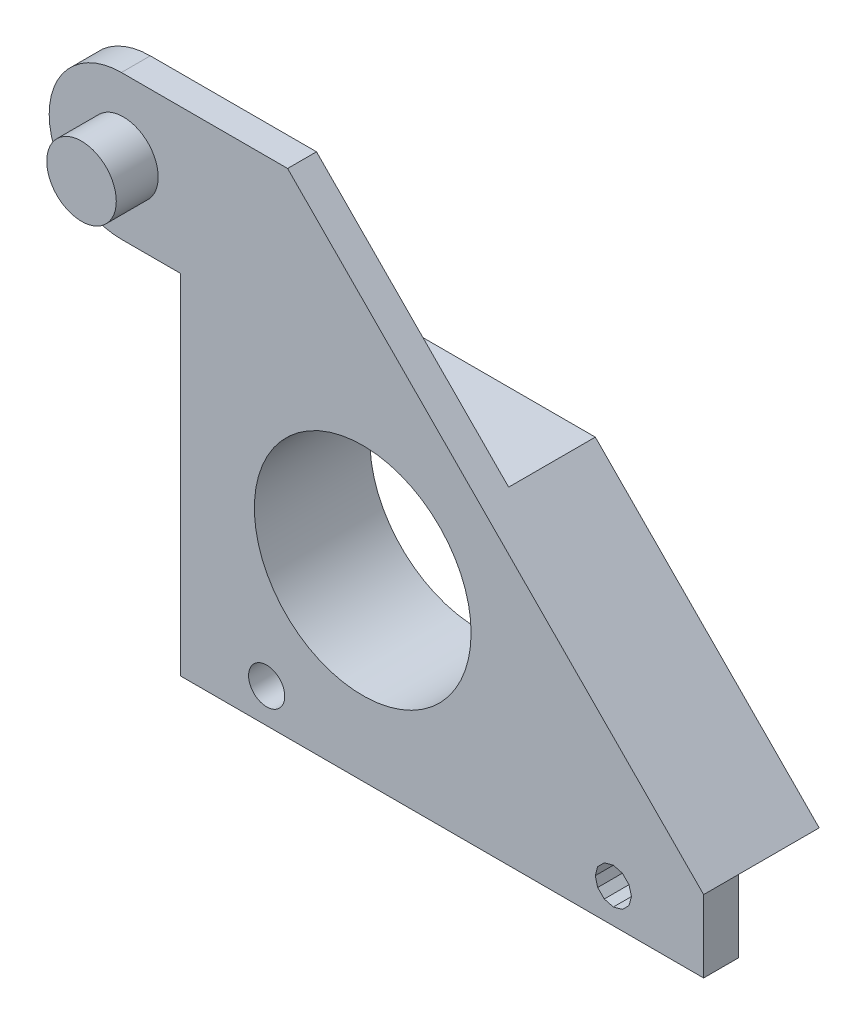
SolidWorks part; units mm, degrees
material "ABS"
ref_plane "Plan de face" through (0, 0, 0) normal (0, 0, 1) x (1, 0, 0)
ref_plane "Plan de dessus" through (0, 0, 0) normal (0, 1, 0) x (1, 0, 0)
ref_plane "Plan de droite" through (0, 0, 0) normal (1, 0, 0) x (0, 0, -1)
ref_plane "Plan1" through (0, 0, 2.4) normal (0, 0, 1) x (1, 0, 0)
sketch "Esquisse4" plane through (0, 0, 2.4) normal (0, 0, 1) x (1, 0, 0)
  line L0 (-20.1, -24.6348) -> (-48.9004, 4.5)
  line L1 (-48.9004, 4.5) -> (-60.4056, 4.5)
  line L2 (-60.4056, 4.5) -> (-61.692, 4.331) construction
  line L3 (-61.692, 4.331) -> (-62.899, 3.831) construction
  line L4 (-62.899, 3.831) -> (-63.935, 3.037) construction
  line L5 (-63.935, 3.037) -> (-64.73, 2.001) construction
  line L6 (-64.73, 2.001) -> (-65.3, 0.625) construction
  line L7 (-65.3, 0.625) -> (-65.3, -1.625) construction
  line L8 (-65.3, -1.625) -> (-64.73, -3.001) construction
  line L9 (-64.73, -3.001) -> (-63.935, -4.037) construction
  line L10 (-63.935, -4.037) -> (-62.899, -4.831) construction
  line L11 (-62.899, -4.831) -> (-61.692, -5.331) construction
  line L12 (-61.692, -5.331) -> (-60.4056, -5.5) construction
  line L13 (-60.4056, -5.5) -> (-56.3, -5.5)
  line L14 (-56.3, -5.5) -> (-56.3, -24.6348)
  line L15 (-56.3, -24.6348) -> (-20.1, -24.6348)
  arc A0 (-60.4056, 4.5) -> (-60.4056, -5.5) centre (-60.2989, -0.5) ccw
extrude "Boss.-Extru.1" add sketch "Esquisse4" against normal blind 2.4
ref_plane "Plan2" through (0, -24.6348, 0) normal (0, -1, 0) x (-1, 0, 0)
sketch "Esquisse9" plane through (0, -24.6348, 0) normal (0, -1, 0) x (-1, 0, 0)
  line L0 (56.3, -2.4) -> (20.1, -2.4)
  line L1 (20.1, -2.4) -> (20.1, 0)
  line L2 (20.1, 0) -> (56.3, 0)
  line L3 (56.3, 0) -> (56.3, -2.4)
extrude "Boss.-Extru.2" add sketch "Esquisse9" along normal blind 5
sketch "Esquisse14" plane through (0, 0, 2.4) normal (0, 0, 1) x (1, 0, 0)
  line L0 (-38.395, -22.305) -> (-37.462, -21.168) construction
  line L1 (-37.462, -21.168) -> (-36.769, -19.871) construction
  line L2 (-36.769, -19.871) -> (-36.342, -18.464) construction
  line L3 (-36.342, -18.464) -> (-36.198, -17) construction
  line L4 (-36.198, -17) -> (-36.7804, -14.9449) construction
  line L5 (-36.7804, -14.9449) -> (-37.2074, -13.5379) construction
  line L6 (-37.2074, -13.5379) -> (-37.9004, -12.2409) construction
  line L7 (-37.9004, -12.2409) -> (-38.3671, -11.6721) construction
  line L8 (-38.3671, -11.6721) -> (-39.532, -10.762) construction
  line L9 (-39.532, -10.762) -> (-40.829, -10.069) construction
  line L10 (-40.829, -10.069) -> (-42.236, -9.642) construction
  line L11 (-42.236, -9.642) -> (-43.7, -9.498) construction
  line L12 (-43.7, -9.498) -> (-45.164, -9.642) construction
  line L13 (-45.164, -9.642) -> (-46.571, -10.069) construction
  line L14 (-46.571, -10.069) -> (-47.868, -10.762) construction
  line L15 (-47.868, -10.762) -> (-49.005, -11.695) construction
  line L16 (-49.005, -11.695) -> (-49.938, -12.832) construction
  line L17 (-49.938, -12.832) -> (-50.631, -14.129) construction
  line L18 (-50.631, -14.129) -> (-51.058, -15.536) construction
  line L19 (-51.058, -15.536) -> (-51.203, -17) construction
  line L20 (-51.203, -17) -> (-51.058, -18.464) construction
  line L21 (-51.058, -18.464) -> (-50.631, -19.871) construction
  line L22 (-50.631, -19.871) -> (-49.938, -21.168) construction
  line L23 (-49.938, -21.168) -> (-49.005, -22.305) construction
  line L24 (-49.005, -22.305) -> (-47.868, -23.238) construction
  line L25 (-47.868, -23.238) -> (-46.571, -23.931) construction
  line L26 (-46.571, -23.931) -> (-45.164, -24.358) construction
  line L27 (-45.164, -24.358) -> (-43.7, -24.502) construction
  line L28 (-43.7, -24.502) -> (-42.236, -24.358) construction
  line L29 (-42.236, -24.358) -> (-40.829, -23.931) construction
  line L30 (-40.829, -23.931) -> (-39.532, -23.238) construction
  line L31 (-39.532, -23.238) -> (-38.395, -22.305) construction
  circle A0 centre (-43.7, -16.9999) radius 7.5023
extrude "Enlèv. mat.-Extru.1" cut sketch "Esquisse14" against normal through all
sketch "Esquisse19" plane through (0, 0, 2.4) normal (0, 0, 1) x (1, 0, 0)
  line L0 (-26.35, -28.503) -> (-25.724, -28.335)
  line L1 (-25.724, -28.335) -> (-25.265, -27.876)
  line L2 (-25.265, -27.876) -> (-25.097, -27.25)
  line L3 (-25.097, -27.25) -> (-25.265, -26.624)
  line L4 (-25.265, -26.624) -> (-25.724, -26.165)
  line L5 (-25.724, -26.165) -> (-26.35, -25.998)
  line L6 (-26.35, -25.998) -> (-26.976, -26.165)
  line L7 (-26.976, -26.165) -> (-27.435, -26.624)
  line L8 (-27.435, -26.624) -> (-27.602, -27.25)
  line L9 (-27.602, -27.25) -> (-27.435, -27.876)
  line L10 (-27.435, -27.876) -> (-26.976, -28.335)
  line L11 (-26.976, -28.335) -> (-26.35, -28.503)
extrude "Enlèv. mat.-Extru.2" cut sketch "Esquisse19" against normal through all
ref_plane "Plan3" through (0, 0, 0) normal (0, 0, -1) x (-1, 0, 0)
sketch "Esquisse25" plane through (0, 0, 0) normal (0, 0, -1) x (-1, 0, 0)
  line L0 (49.265, -26.624) -> (49.097, -27.25) construction
  line L1 (49.097, -27.25) -> (49.265, -27.876) construction
  line L2 (49.265, -27.876) -> (49.724, -28.335) construction
  line L3 (49.724, -28.335) -> (50.35, -28.503) construction
  line L4 (50.35, -28.503) -> (50.976, -28.335) construction
  line L5 (50.976, -28.335) -> (51.435, -27.876) construction
  line L6 (51.435, -27.876) -> (51.602, -27.25) construction
  line L7 (51.602, -27.25) -> (51.2358, -26.3644) construction
  line L8 (51.2358, -26.3644) -> (51.0062, -26.1348) construction
  line L9 (51.0062, -26.1348) -> (50.35, -25.998) construction
  line L10 (50.35, -25.998) -> (49.724, -26.165) construction
  line L11 (49.724, -26.165) -> (49.265, -26.624) construction
  circle A0 centre (50.35, -27.2502) radius 1.2528
extrude "Enlèv. mat.-Extru.3" cut sketch "Esquisse25" against normal through all
sketch "Esquisse28" plane through (0, 0, 2.4) normal (0, 0, 1) x (1, 0, 0)
  circle A0 centre (-60.2677, -0.4991) radius 2.407
extrude "Boss.-Extru.3" add sketch "Esquisse28" along normal blind 2.9
sketch "Sketch1" plane through (0, 0, 2.4) normal (0, 0, 1) x (1, 0, 0)
  line L0 (-43.7, -16.9999) -> (-36.1977, -16.9999) construction
  line L1 (-50.35, -27.2502) -> (-20.1, -27.1348) construction
  line L2 (-20.1, -29.6348) -> (-20.1, -24.6348) construction
  line L3 (-26.35, -28.503) -> (-26.35, -25.998) construction
  line L4 (-56.3, -24.6348) -> (-56.3, -5.5)
  line L5 (-56.3, -5.5) -> (-56.3, -29.6348) construction
  line L6 (-56.3, -5.5) -> (-60.4056, -5.5)
  line L7 (-60.4056, 4.5) -> (-48.9004, 4.5)
  line L8 (-48.9004, 4.5) -> (-20.1, -24.6348)
  line L9 (-20.1, -24.6348) -> (-48.9004, 4.5) construction
  line L13 (-20.1, -24.6348) -> (-56.3, -24.6348)
  circle A1 centre (-43.7, -16.9999) radius 7.5023 construction
  circle A2 centre (-43.7, -16.9999) radius 7.5023
  arc A4 (-60.4056, -5.5) -> (-60.4056, 4.5) centre (-60.4056, -0.5) cw
extrude "Boss-Extrude1" add sketch "Sketch1" against normal blind 8
sketch "Sketch2" plane through (0, -24.6348, 0) normal (0, -1, 0) x (1, 0, 0)
  line L1 (-56.3, 0) -> (-20.1, 0)
  line L2 (-56.3, 0) -> (-56.3, -5.6)
  line L3 (-56.3, -5.6) -> (-20.1, -5.6)
  line L4 (-20.1, 0) -> (-20.1, -5.6)
sketch "Sketch3" plane through (0, 0, -5.6) normal (0, 0, -1) x (-1, 0, 0)
  line L5 (56.3, -8.9561) -> (56.3, -5.5)
  line L6 (56.3, -5.5) -> (60.4056, -5.5)
  line L7 (35.5987, -8.9561) -> (48.9004, 4.5)
  line L8 (48.9004, 4.5) -> (60.4056, 4.5)
  line L9 (35.5987, -8.9561) -> (56.3, -8.9561)
  arc A1 (60.4056, 4.5) -> (60.4056, -5.5) centre (60.4056, -0.5) cw
  dimension "D1" = 20.7013
  dimension "D2" = 18.9209
extrude "Cut-Extrude2" cut sketch "Sketch3" against normal blind 6
